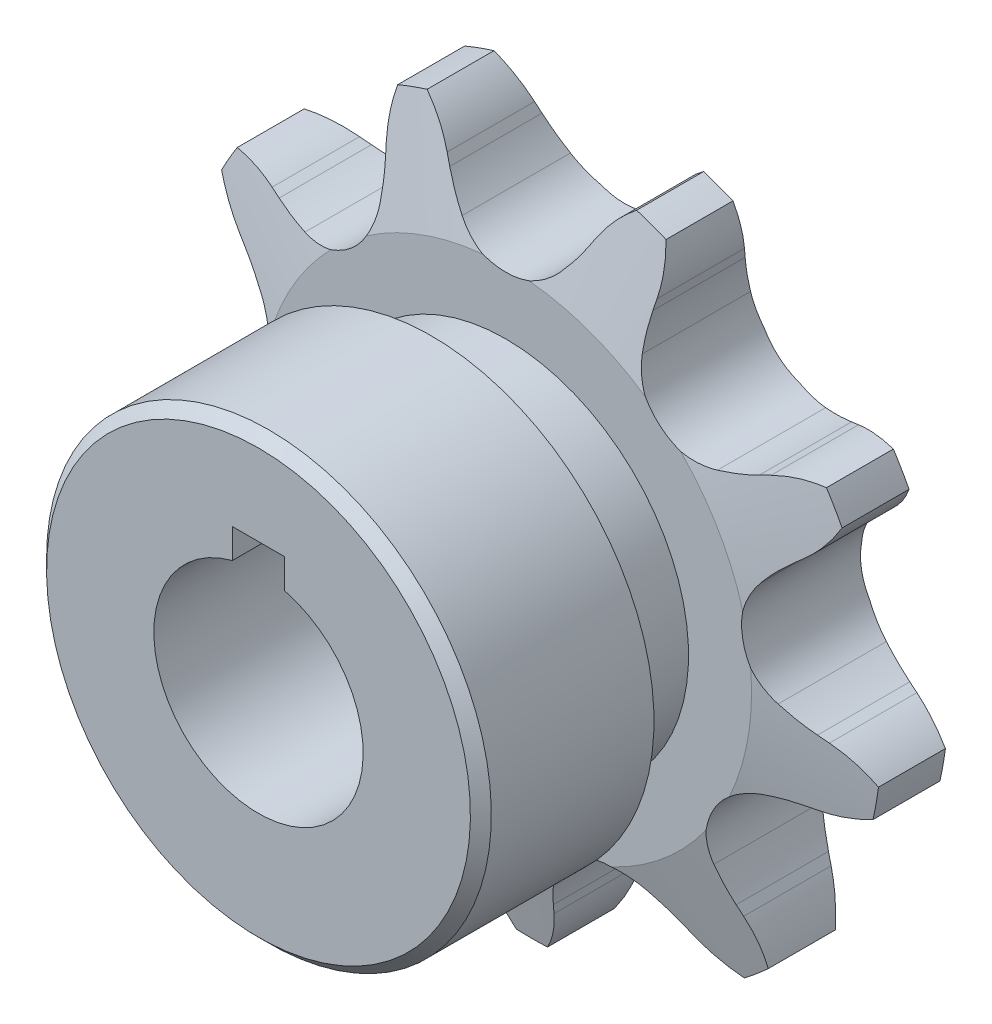
SolidWorks part; units mm, degrees
material "AISI 1045 Steel, cold drawn"
ref_plane "Front Plane" through (0, 0, 0) normal (0, 0, 1) x (1, 0, 0)
ref_plane "Top Plane" through (0, 0, 0) normal (0, 1, 0) x (1, 0, 0)
ref_plane "Right Plane" through (0, 0, 0) normal (1, 0, 0) x (0, 0, -1)
sketch "Sketch0" plane through (0, 0, 0) normal (0, 0, 1) x (1, 0, 0)
  line L0 (6.35, -17.4465) -> (0, 0) construction
  line L1 (0, 0) -> (16.0788, -9.2831) construction
  line L2 (0, 0) -> (-6.35, -17.4465) construction
  line L3 (6.35, -17.4465) -> (16.0788, -9.2831) construction
  line L4 (6.35, -17.4465) -> (-6.35, -17.4465) construction
  line L5 (10.4598, -15.5253) -> (9.9923, -15.1314)
  line L6 (6.35, -17.4465) -> (0, -19.7577) construction
  line L7 (1.9668, -18.6165) -> (2.0717, -18.0142)
  line L8 (0, -17.4465) -> (0, -21.2565) construction
  line L9 (8.2407, -13.94) -> (3.3411, -23.0268) construction
  line L10 (0, 0) -> (0, -17.4465) construction
  line L11 (9.9923, -15.1314) -> (3.3411, -23.0268) construction
  line L12 (0, -21.2565) -> (0, -22.3353) construction
  line L13 (14.849, -10.3149) -> (10.4598, -15.5253) construction
  circle A0 centre (0, 0) radius 21.2565 construction
  circle A1 centre (0, 0) radius 18.5662 construction
  arc A2 (-6.5326, -24.0204) -> (20.4442, -14.2017) centre (0, 0) ccw
  circle A3 centre (0, 0) radius 22.3353 construction
  circle A4 centre (6.35, -17.4465) radius 3.9624 construction
  arc A7 (8.2407, -13.94) -> (2.6477, -15.9757) centre (6.35, -17.4465) ccw
  circle A8 centre (6.35, -17.4465) radius 3.9837 construction
  arc A9 (10.4598, -15.5253) -> (20.4442, -14.2017) centre (14.849, -10.3149) ccw
  arc A10 (9.9923, -15.1314) -> (8.2407, -13.94) centre (3.3411, -23.0268) ccw
  arc A11 (1.9668, -18.6165) -> (-6.5326, -24.0204) centre (-4.7447, -17.4465) cw
  arc A12 (2.0717, -18.0142) -> (2.6477, -15.9757) centre (12.2419, -19.7872) cw
  dimension "D1" = 3.9837
  dimension "R" = 3.9837
sketch "Sketch1" plane through (0, 0, 0) normal (1, 0, 0) x (0, 0, -1)
  line L0 (3.6068, 0) -> (-3.6068, 0)
  line L1 (-3.6068, 0) -> (-3.6068, 14.9065)
  line L2 (-3.6068, 14.9065) -> (-2.0193, 21.2565)
  line L3 (-2.0193, 21.2565) -> (2.0193, 21.2565)
  line L4 (2.0193, 21.2565) -> (3.6068, 14.9065)
  line L5 (3.6068, 14.9065) -> (3.6068, 0)
  line L7 (0, 21.2565) -> (0, 0) construction
  line L8 (-3.6068, 14.9065) -> (3.6068, 14.9065) construction
  line L9 (0, 21.2565) -> (0, -21.2565) construction
  line L10 (-3.6068, 14.9065) -> (-3.6068, 21.2565) construction
  line L11 (-3.6068, 21.2565) -> (-2.0193, 21.2565) construction
  line L12 (2.0193, 21.2565) -> (3.6068, 21.2565) construction
  line L13 (3.6068, 21.2565) -> (3.6068, 14.9065) construction
  line L22 (3.6068, 0) -> (-18.6182, 0) construction
  line L24 (-3.6068, 0) -> (-3.6068, 11.0815) construction
revolve "Revolve1" add sketch "Sketch1" angle 360 mid plane about L0
extrude "Cut-Extrude1" cut sketch "Sketch0" against normal through all and the other way through all
pattern_circular "CirPattern1" count 9 over 360 about axis through (0, 0, 0) along (0, 0, 1) of "Cut-Extrude1"
sketch "Sketch2" plane through (0, 0, 0) normal (0, 0, 1) x (1, 0, 0)
  line L0 (0, 13.4937) -> (0, 6.35) construction
  line L1 (0, 0) -> (13.4937, 0) construction
  line L2 (0, 6.35) -> (0, 0) construction
  circle A0 centre (0, 0) radius 6.35 construction
  circle A1 centre (0, 0) radius 13.4938
  circle A2 centre (0, 0) radius 21.209 construction
  dimension "Bore" = 12.7
  dimension "Hub Dia." = 26.9875
  dimension "OD" = 42.418
extrude "Bore/OD/HubDiameter" add sketch "Sketch2" along normal up to vertex (18.6182 mm away) from surface at 3.6068 starting at face at (0, 0, 3.6068)
sketch "Sketch3" plane through (0, 0, 0) normal (0, 0, 1) x (1, 0, 0)
  circle A0 centre (0, 0) radius 6.35 construction
  circle A1 centre (0, 0) radius 6.35
  circle A2 centre (0, 0) radius 21.209 construction
  circle A3 centre (0, 0) radius 21.209
extrude "Cut-Extrude2" cut sketch "Sketch3" along normal through all and the other way through all flip side to cut
sketch "Sketch4" plane through (0, 0, 0) normal (1, 0, 0) x (0, 0, -1)
  line L0 (-18.6182, 13.4937) -> (-18.6182, 12.8587)
  line L1 (-3.6068, 21.2565) -> (-8.1153, 21.2565)
  line L2 (-3.6068, 21.2565) -> (-3.6068, 11.0815)
  line L3 (-3.6068, 11.0815) -> (-8.1153, 11.0815)
  line L4 (-8.1153, 21.2565) -> (-8.1153, 11.0815)
  line L9 (-18.6182, 12.8587) -> (-17.9832, 13.4938)
  line L10 (-17.9832, 13.4938) -> (-18.6182, 13.4937)
  dimension "C" = 0.635
  dimension "D3" = 4.5085
revolve "Cut-Revolve1" cut sketch "Sketch4" angle 360 mid plane about L22
sketch "Sketch5" plane through (0, 0, -3.6068) normal (0, 0, -1) x (-1, 0, 0)
  line L0 (0, 4.7625) -> (0, 0) construction
  line L1 (1.5875, 7.9375) -> (-1.5875, 7.9375)
  line L2 (1.5875, 7.9375) -> (1.5875, 4.7625)
  line L3 (1.5875, 4.7625) -> (-1.5875, 4.7625)
  line L4 (-1.5875, 7.9375) -> (-1.5875, 4.7625)
  line L5 (1.5875, 6.35) -> (-1.5875, 6.35) construction
  dimension "Key Wd." = 3.175
  dimension "Key Ht." = 1.5875
extrude "Keyway" cut sketch "Sketch5" against normal through all
equation "\"360/N@Sketch0\" = 360/\"Teeth@CirPattern1\""
equation "\"Ds@Sketch0\" = 1.005 * \"Dr@Sketch0\" + 0.003"
equation "\"R@Sketch0\" = 1/2 * \"Ds@Sketch0\""
equation "\"A@Sketch0\" = 35 +  ( 60 / \"Teeth@CirPattern1\" ) "
equation "\"B@Sketch0\" = 18 -  ( 56 / \"Teeth@CirPattern1\" )"
equation "\"ac@Sketch0\" = 0.8 * \"Dr@Sketch0\""
equation "\"ab@Sketch0\" = 1.4 * \"Dr@Sketch0\""
equation "\"J@Sketch0\" = 0.3 * \"Pitch@Sketch0\""
equation "\"h@Sketch1\" = \"Pitch@Sketch0\" / 2"
equation "\"g@Sketch1\" = \"h@Sketch1\" / 4"
equation "\"MHD@Sketch1\" = \"Pitch@Sketch0\" * ( cotan ( 180 / \"Teeth@CirPattern1\" ) - 1 ) - 0.030"
equation "\"D3@Sketch4\" = \"t@Sketch1\" * 5 / 8"
